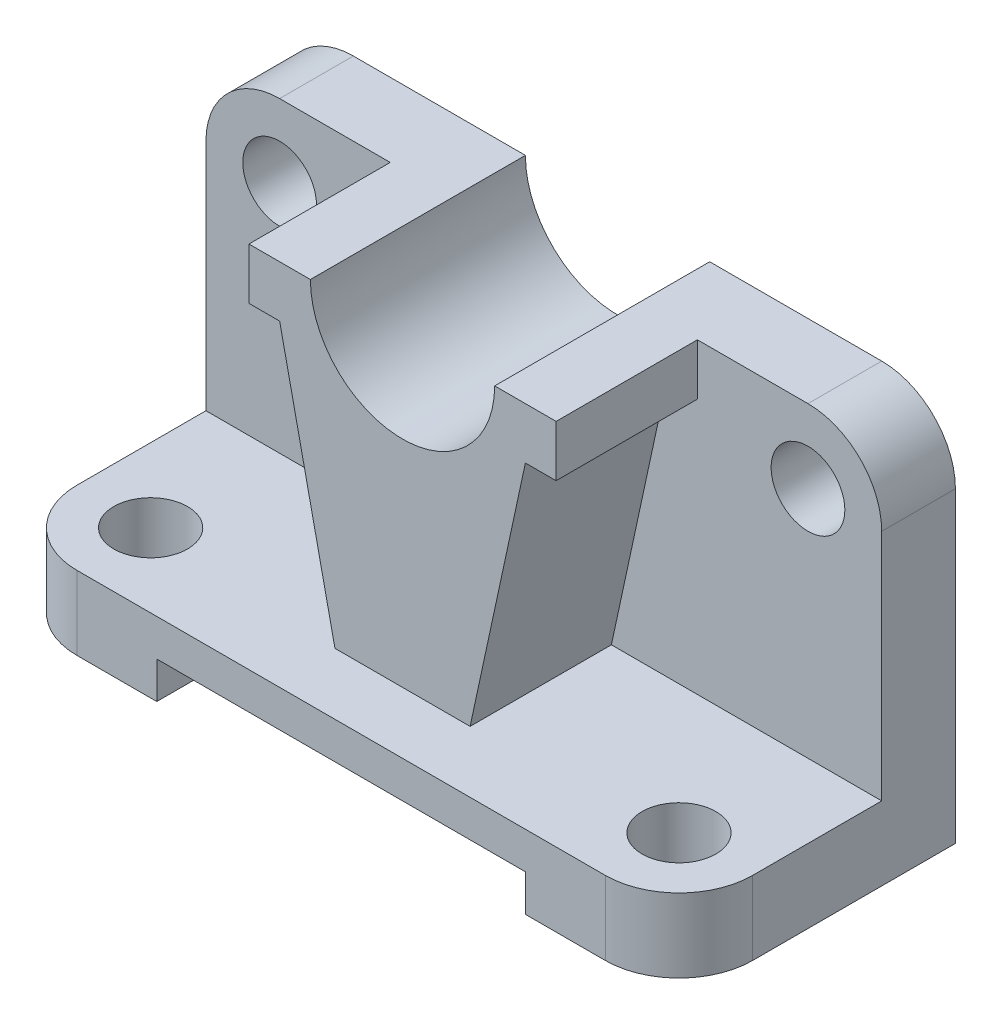
SolidWorks part; units mm, degrees
ref_plane "Front Plane" through (0, 0, 0) normal (0, 0, 1) x (1, 0, 0)
ref_plane "Top Plane" through (0, 0, 0) normal (0, 1, 0) x (1, 0, 0)
ref_plane "Right Plane" through (0, 0, 0) normal (1, 0, 0) x (0, 0, -1)
sketch "Sketch1" plane through (0, 0, 0) normal (0, 0, 1) x (1, 0, 0)
  line L1 (0, 0) -> (110, 0)
  line L2 (0, 0) -> (0, 62)
  line L3 (0, 62) -> (110, 62)
  line L4 (110, 0) -> (110, 62)
  dimension "D1" = 110
  dimension "D2" = 62
extrude "Boss-Extrude1" add sketch "Sketch1" along normal blind 12
sketch "Sketch2" plane through (0, 0, 12) normal (0, 0, 1) x (1, 0, 0)
  line L0 (110, 0) -> (110, 62) construction
  line L1 (0, 0) -> (110, 0)
  line L2 (0, 0) -> (0, 12)
  line L3 (0, 12) -> (110, 12)
  line L4 (110, 0) -> (110, 12)
  dimension "D1" = 12
extrude "Boss-Extrude2" add sketch "Sketch2" along normal blind 33
sketch "Sketch3" plane through (0, 0, 12) normal (0, 0, 1) x (1, 0, 0)
  line L0 (110, 62) -> (0, 62) construction
  line L1 (30, 62) -> (80, 62)
  line L2 (30, 62) -> (30, 53.6344)
  line L3 (30, 53.6344) -> (80, 53.6344)
  line L4 (80, 62) -> (80, 53.6344)
  line L5 (0, 62) -> (0, 12) construction
  line L6 (110, 12) -> (110, 62) construction
  line L7 (35, 53.6344) -> (44, 12)
  line L8 (110, 12) -> (0, 12) construction
  line L9 (44, 12) -> (66, 12)
  line L10 (66, 12) -> (75, 53.6344)
  line L11 (110, 0) -> (110, 12) construction
  line M3 (0, 12) -> (110, 12)
  line M5 (110, 62) -> (0, 62)
  dimension "D1" = 30
  dimension "D2" = 30
  dimension "D3" = 44
  dimension "D4" = 44
  dimension "D5" = 5
  dimension "D6" = 5
extrude "Boss-Extrude3" add sketch "Sketch3" along normal blind 23 contours L10 L3 L7 M3 | L4 L2 L3 M5
sketch "Sketch7" plane through (0, 0, 12) normal (0, 0, 1) x (1, 0, 0)
  line L0 (30, 62) -> (0, 62) construction
  line L2 (0, 62) -> (0, 12) construction
  circle A0 centre (12, 50) radius 6
  dimension "D1" = 12
  dimension "D2" = 12
  dimension "D3" = 12
extrude "Cut-Extrude8" cut sketch "Sketch7" against normal through all
sketch "Sketch9" plane through (0, 0, 12) normal (0, 0, 1) x (1, 0, 0)
  circle A0 centre (98, 50) radius 6
extrude "Cut-Extrude9" cut sketch "Sketch9" against normal through all
sketch "Sketch10" plane through (0, 12, 0) normal (0, 1, 0) x (1, 0, 0)
  circle A0 centre (12, -33) radius 6
extrude "Cut-Extrude10" cut sketch "Sketch10" against normal through all
sketch "Sketch11" plane through (0, 12, 0) normal (0, 1, 0) x (1, 0, 0)
  circle A0 centre (98, -33) radius 6
extrude "Cut-Extrude11" cut sketch "Sketch11" against normal through all
sketch "Sketch15" plane through (0, 0, 45) normal (0, 0, 1) x (1, 0, 0)
  line L0 (0, 0) -> (110, 0) construction
  line L1 (25, 6) -> (85, 6)
  line L2 (25, 6) -> (25, 0)
  line L3 (25, 0) -> (85, 0)
  line L4 (85, 6) -> (85, 0)
  dimension "D1" = 6
  dimension "D2" = 25
  dimension "D3" = 60
extrude "Cut-Extrude15" cut sketch "Sketch15" against normal through all
fillet "Fillet3" radius 12 4 edges at (0, 6, 45) (110, 6, 45) (110, 62, 6) (0, 62, 6)
sketch "Sketch16" plane through (0, 0, 35) normal (0, 0, 1) x (1, 0, 0)
  line L0 (80, 62) -> (30, 62) construction
  circle A0 centre (55, 62) radius 15
extrude "Cut-Extrude16" cut sketch "Sketch16" against normal through all
